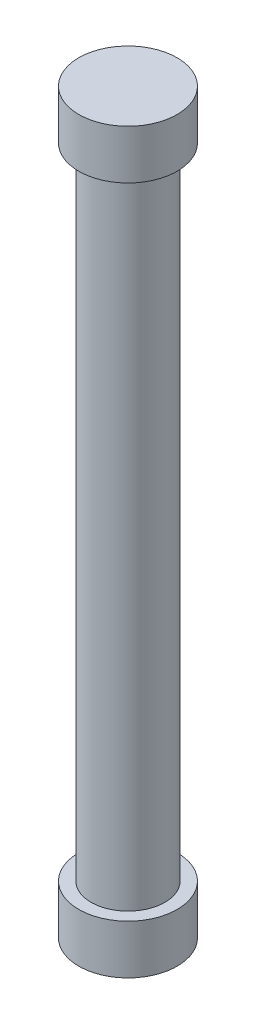
SolidWorks part; units mm, degrees
ref_plane "Front Plane" through (0, 0, 0) normal (0, 0, 1) x (1, 0, 0)
ref_plane "Top Plane" through (0, 0, 0) normal (0, 1, 0) x (1, 0, 0)
ref_plane "Right Plane" through (0, 0, 0) normal (1, 0, 0) x (0, 0, -1)
sketch "Sketch1" plane through (0, 0, 0) normal (0, 0, 1) x (1, 0, 0)
  line L0 (0, 23.3) -> (0, -6.7)
  line L1 (0, -6.7) -> (-2, -6.7)
  line L2 (-2, -6.7) -> (-2, -4.7)
  line L3 (-2, -4.7) -> (-1.5, -4.7)
  line L4 (-1.5, -4.7) -> (-1.5, 21.3)
  line L5 (-1.5, 21.3) -> (-2, 21.3)
  line L6 (-2, 21.3) -> (-2, 23.3)
  line L7 (-2, 23.3) -> (0, 23.3)
  dimension "D1" = 1.5
  dimension "D2" = 2
  dimension "D3" = 2
  dimension "D4" = 2
  dimension "D5" = 2
  dimension "D6" = 30
sketch "Sketch3" plane through (0, 0, 0) normal (0, 0, 1) x (1, 0, 0)
revolve "Revolve1" add sketch "Sketch1" angle 360 about L0
